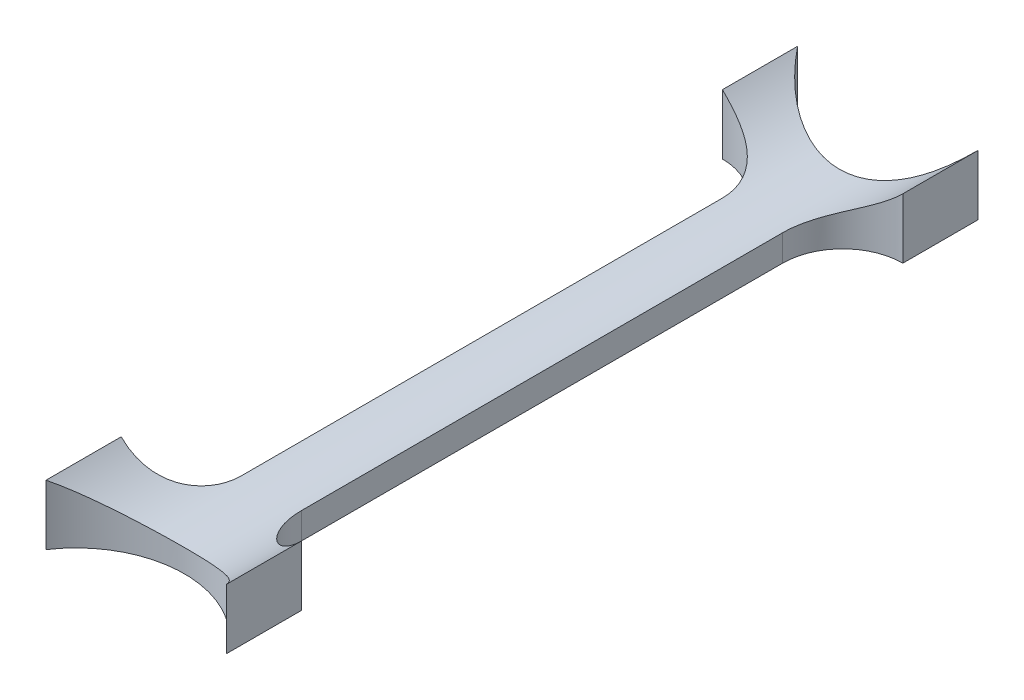
SolidWorks part; units mm, degrees
ref_plane "Plan de face" through (0, 0, 0) normal (0, 0, 1) x (1, 0, 0)
ref_plane "Plan de dessus" through (0, 0, 0) normal (0, 1, 0) x (1, 0, 0)
ref_plane "Plan de droite" through (0, 0, 0) normal (1, 0, 0) x (0, 0, -1)
sketch "Esquisse1" plane through (0, 0, 0) normal (0, 1, 0) x (1, 0, 0)
  line L0 (0, 62.5) -> (0, -62.5) construction
  line L1 (15, 62.5) -> (-15, 62.5) construction
  line L2 (15, 62.5) -> (15, -62.5) construction
  line L3 (15, -62.5) -> (-15, -62.5) construction
  line L4 (-15, 62.5) -> (-15, -62.5) construction
  line L5 (15, 62.5) -> (-15, -62.5) construction
  line L6 (15, -62.5) -> (-15, 62.5) construction
  line L7 (-5, 62.5) -> (-5, -62.5) construction
  line L8 (5, 62.5) -> (5, -62.5) construction
  line L9 (15, 0) -> (-15, 0) construction
  line L10 (-15, 62.5) -> (-15, 50)
  line L11 (-5, 40) -> (-5, -40)
  line L12 (15, 62.5) -> (15, 50)
  line L13 (5, 40) -> (5, -40)
  line L14 (15, -62.5) -> (15, -50)
  line L15 (-15, -62.5) -> (-15, -50)
  arc A0 (-15, 62.5) -> (15, 62.5) centre (0, 72.5) ccw
  arc A1 (-15, 50) -> (-5, 40) centre (-15, 40) cw
  arc A2 (15, 50) -> (5, 40) centre (15, 40) ccw
  arc A3 (15, -50) -> (5, -40) centre (15, -40) cw
  arc A4 (-15, -62.5) -> (15, -62.5) centre (0, -72.5) cw
  arc A5 (-15, -50) -> (-5, -40) centre (-15, -40) ccw
  point P0 (0, 0)
  point P21 (0, 0)
  point P22 (-5, 24.2596)
  point P29 (5, 0)
  point P32 (-5, 0)
  dimension "D4" = 10
  dimension "D5" = 10
  dimension "D1" = 125
  dimension "D2" = 30
  dimension "D3" = 10
  dimension "D6" = 12.5
extrude "Boss.-Extru.1" add sketch "Esquisse1" along normal blind 10
sketch "Esquisse2" plane through (0, 0, 0) normal (0, 0, 1) x (1, 0, 0)
  line L0 (0, 0) -> (0, 13.7795) construction
  line L4 (-15, 0) -> (15, 0)
  line L5 (15, 0) -> (15, 10)
  line L6 (15, 10) -> (-15, 10)
  line L7 (-15, 10) -> (-15, 0)
  line L8 (-15, 0) -> (15, 0)
  line L9 (15, 0) -> (15, 10)
  line L10 (15, 10) -> (-15, 10)
  line L11 (-15, 10) -> (-15, 0)
  arc A0 (-15, 10) -> (15, 10) centre (0, 25) ccw
  dimension "D2" = 15
  dimension "D1" = 0
extrude "Enlèv. mat.-Extru.1" cut sketch "Esquisse2" against normal through all both and the other way through all contours A0 L0 L10 | L0 A0 L10
